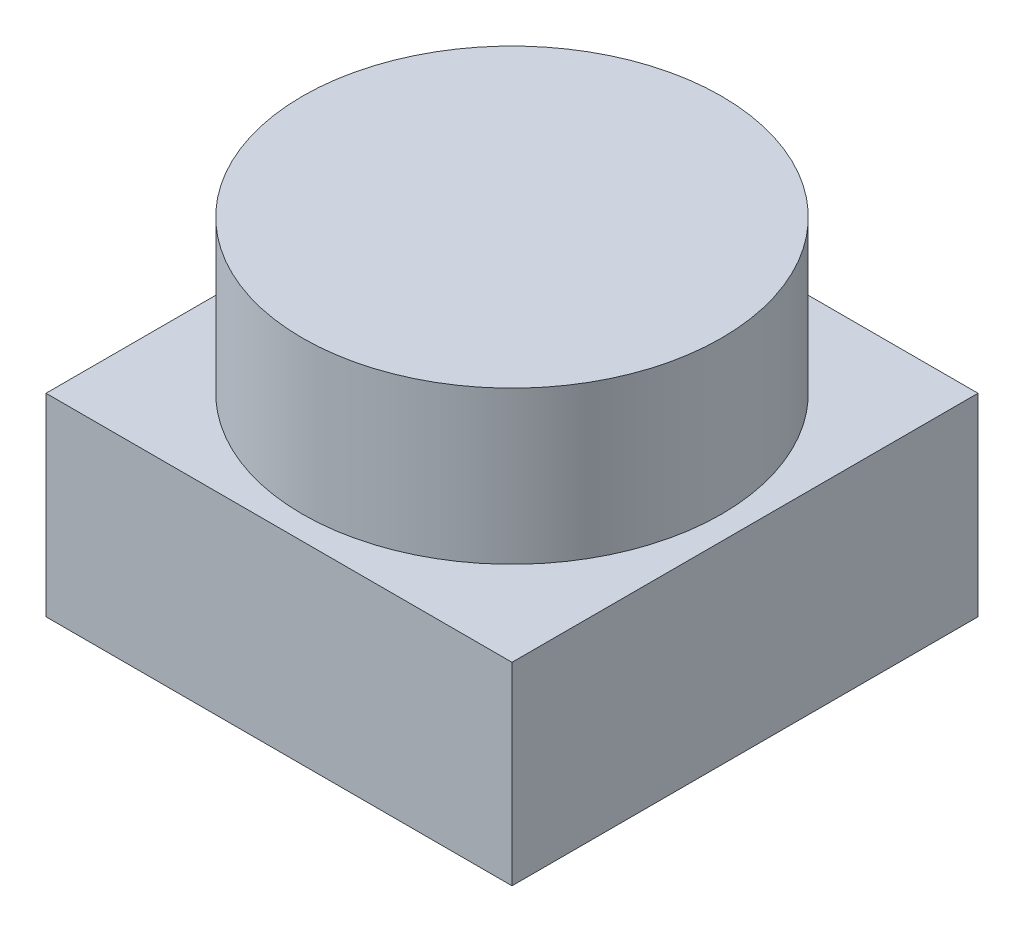
SolidWorks part; units mm, degrees
ref_plane "Front Plane" through (0, 0, 0) normal (0, 0, 1) x (1, 0, 0)
ref_plane "Top Plane" through (0, 0, 0) normal (0, 1, 0) x (1, 0, 0)
ref_plane "Right Plane" through (0, 0, 0) normal (1, 0, 0) x (0, 0, -1)
sketch "Sketch1" plane through (0, 0, 0) normal (0, 1, 0) x (1, 0, 0)
  line L1 (-27.8, 27.8) -> (27.8, 27.8)
  line L2 (-27.8, 27.8) -> (-27.8, -27.8)
  line L3 (-27.8, -27.8) -> (27.8, -27.8)
  line L4 (27.8, 27.8) -> (27.8, -27.8)
  line L5 (-27.8, 27.8) -> (27.8, -27.8) construction
  line L6 (-27.8, -27.8) -> (27.8, 27.8) construction
  point P0 (0, 0)
  dimension "D1" = 55.6
extrude "Boss-Extrude1" add sketch "Sketch1" along normal blind 23.1
sketch "Sketch2" plane through (0, 23.1, 0) normal (0, 1, 0) x (1, 0, 0)
  circle A0 centre (0, 0) radius 25
  dimension "D1" = 50
extrude "Boss-Extrude2" add sketch "Sketch2" along normal blind 18.2
sketch "Sketch3" plane through (0, 0, 0) normal (0, -1, 0) x (1, 0, 0)
  circle A0 centre (-21.5, 21.5) radius 1.5
  circle A1 centre (21.5, 21.5) radius 1.5
  circle A2 centre (-21.5, -21.5) radius 1.5
  circle A3 centre (21.5, -21.5) radius 1.5
  point P8 (-22.5868, 21.2632)
  dimension "D1" = 3
  dimension "D2" = 43
  dimension "D3" = 43
  dimension "D4" = 21.5
  dimension "D5" = 21.5
extrude "Cut-Extrude1" cut sketch "Sketch3" against normal blind 7
